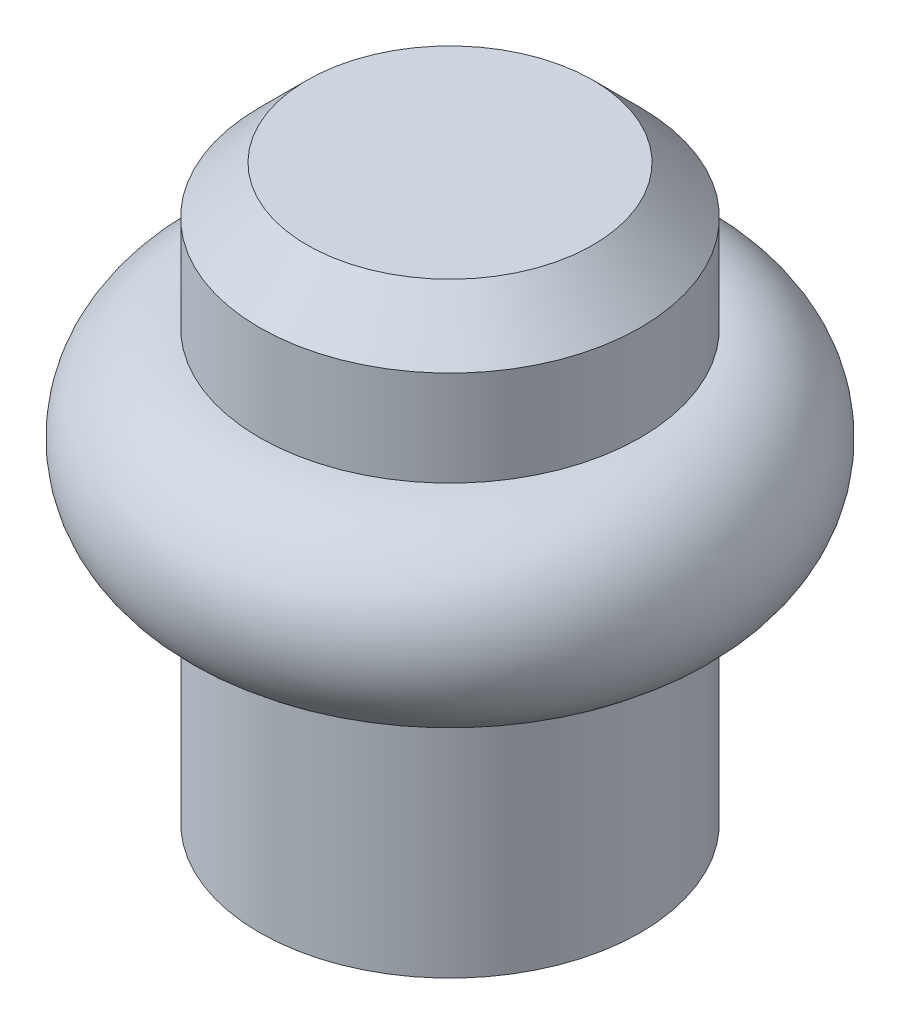
SolidWorks part; units mm, degrees
ref_plane "Front Plane" through (0, 0, 0) normal (0, 0, 1) x (1, 0, 0)
ref_plane "Top Plane" through (0, 0, 0) normal (0, 1, 0) x (1, 0, 0)
ref_plane "Right Plane" through (0, 0, 0) normal (1, 0, 0) x (0, 0, -1)
sketch "Sketch1" plane through (0, 0, 0) normal (1, 0, 0) x (0, 0, -1)
  line L0 (0, 0) -> (0, 3.7348) construction
  line L1 (0, 0) -> (0, 3)
  line L2 (0, 3) -> (-0.75, 3)
  line L3 (-0.75, 3) -> (-1, 2.75)
  line L4 (-1, 2.75) -> (-1, 2.25)
  line L5 (-1, 0) -> (0, 0)
  line L6 (-1, 1.25) -> (-1, 0)
  arc A0 (-1, 2.25) -> (-1, 1.25) centre (-1, 1.75) ccw
  dimension "D5" = 1
  dimension "D1" = 3
  dimension "D2" = 2
  dimension "D3" = 135
  dimension "D4" = 0.25
  dimension "D6" = 1.75
revolve "Revolve1" add sketch "Sketch1" angle 360 about L0
